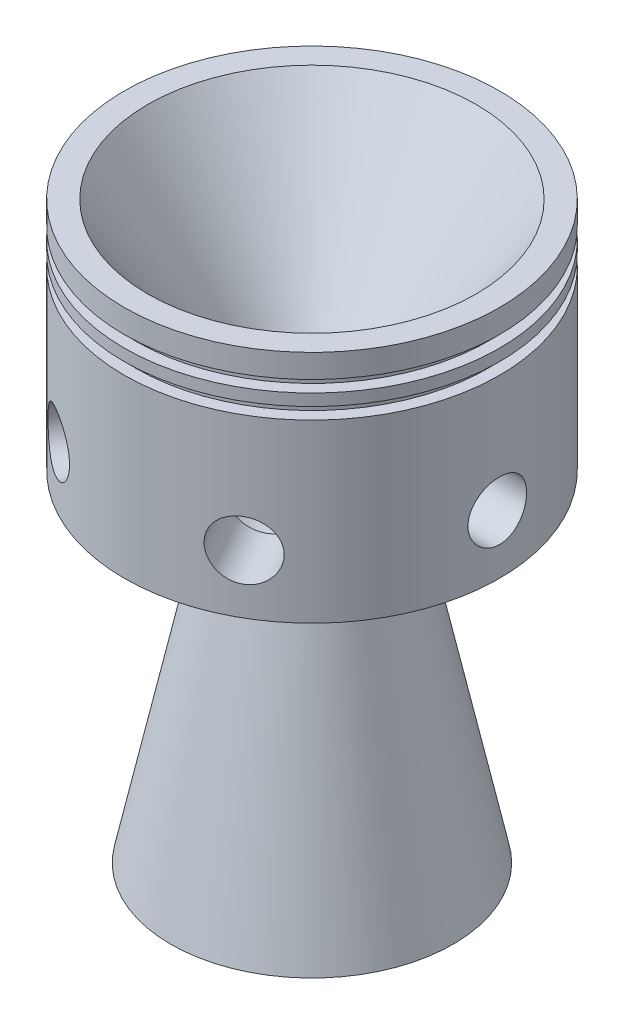
SolidWorks part; units mm, degrees
ref_plane "Front Plane" through (0, 0, 0) normal (0, 0, 1) x (1, 0, 0)
ref_plane "Top Plane" through (0, 0, 0) normal (0, 1, 0) x (1, 0, 0)
ref_plane "Right Plane" through (0, 0, 0) normal (1, 0, 0) x (0, 0, -1)
sketch "Sketch1" plane through (0, 0, 0) normal (0, 0, 1) x (1, 0, 0)
  line L0 (0, 0) -> (2.54, 0)
  line L8 (0, 0) -> (0, -2.54)
  line L9 (0, -2.54) -> (1.27, -2.54)
  line L10 (1.27, -2.54) -> (1.27, -3.81)
  line L11 (1.27, -3.81) -> (0, -3.81)
  line L12 (0, -3.81) -> (0, -5.08)
  line L13 (0, -5.08) -> (1.27, -5.08)
  line L14 (1.27, -5.08) -> (1.27, -6.35)
  line L15 (1.27, -6.35) -> (0, -6.35)
  line L16 (0, -6.35) -> (0, -25.4)
  line L17 (0, -25.4) -> (12.8551, -25.4)
  line L18 (0, 0) -> (20.32, 0) construction
  line L19 (20.32, 0) -> (20.32, -62.23) construction
  line L20 (2.54, 0) -> (16.129, -19.4071)
  line L22 (7.5666, -62.23) -> (5.0266, -62.23)
  line L23 (5.0266, -62.23) -> (12.8551, -25.4)
  line L24 (16.129, -19.4071) -> (16.129, -21.9471)
  line L25 (16.129, -21.9471) -> (7.5666, -62.23)
  line L26 (5.0266, -62.23) -> (5.0266, -25.4) construction
  line L27 (20.32, -62.23) -> (7.5666, -62.23) construction
  dimension "D1" = 2.54
  dimension "D2" = 1.27
  dimension "D3" = 1.27
  dimension "D4" = 2.54
  dimension "D5" = 1.27
  dimension "D6" = 20.32
  dimension "D7" = 2.54
  dimension "D8" = 35
  dimension "D9" = 12
  dimension "D10" = 2.54
  dimension "D11" = 4.191
  dimension "D12" = 25.4
  dimension "D13" = 36.83
  dimension "D14" = 62.23
  dimension "D15" = 15.2934
revolve "base_revolve" add sketch "Sketch1" angle 360 about L19
ref_plane "Plane1" through (40.64, 0, 0) normal (1, 0, 0) x (0, 0, -1)
sketch "Sketch2" plane through (40.64, 0, 0) normal (1, 0, 0) x (0, 0, -1)
  line L0 (0, 0) -> (0, -19.05) construction
  point P4 (0, -19.05)
  dimension "D2" = 19.05
hole_wizard "1/4 (0.25) Diameter Hole1" positions "Sketch2" profile "Sketch3" hole size "1/4" standard "ANSI Inch"
sketch "Sketch3" plane through (40.64, -19.05, 0) normal (0, 1, 0) x (0, 0, -1)
  line L0 (0, 0) -> (0, 8.89)
  line L1 (0, 8.89) -> (3.175, 6.9823)
  line L2 (3.175, 6.9823) -> (3.175, 0)
  line L5 (3.175, 0) -> (0, 0)
  line L10 (0, 8.89) -> (-3.175, 6.9823) construction
  line L11 (0, -6.35) -> (0, 107.95) construction
  dimension "Hole Dia." = 6.35
  dimension "Hole Depth" = 8.89
  dimension "Drill Angle" = 118
pattern_circular "radial_bolts" count 6 over 360 about axis through (20.32, 0, 0) along (0, 1, 0) of "1/4 (0.25) Diameter Hole1"
